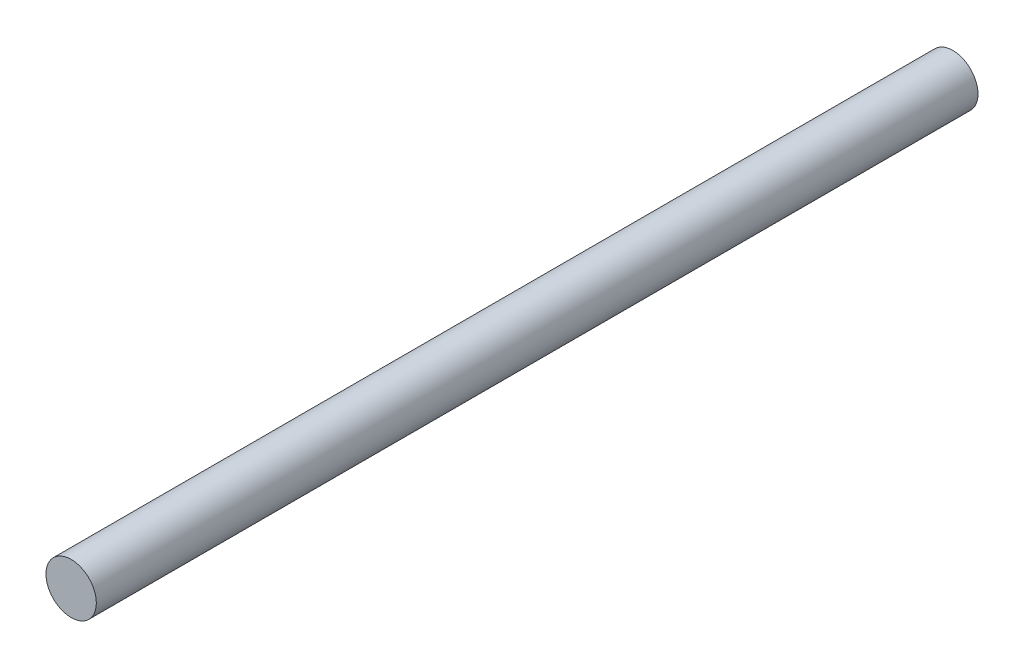
SolidWorks part; units mm, degrees
ref_plane "Front Plane" through (0, 0, 0) normal (0, 0, 1) x (1, 0, 0)
ref_plane "Top Plane" through (0, 0, 0) normal (0, 1, 0) x (1, 0, 0)
ref_plane "Right Plane" through (0, 0, 0) normal (1, 0, 0) x (0, 0, -1)
sketch "Sketch1" plane through (0, 0, 0) normal (0, 0, 1) x (1, 0, 0)
  circle A0 centre (0, 0) radius 3
  dimension "D1" = 6
extrude "Boss-Extrude1" add sketch "Sketch1" along normal blind 105
